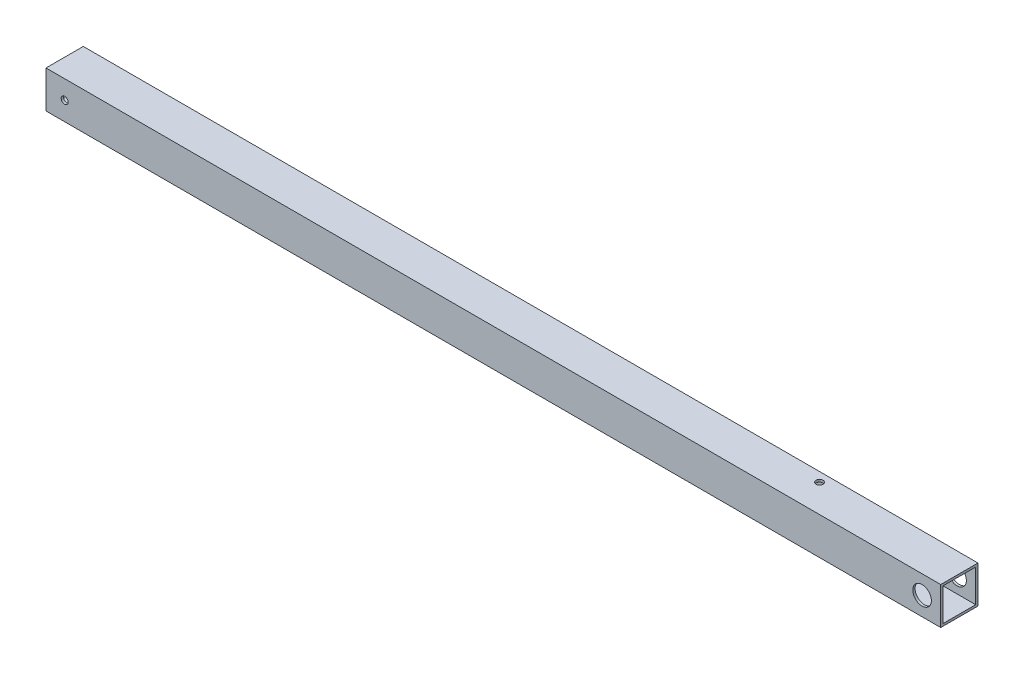
SolidWorks part; units mm, degrees
material "1060 Alloy"
ref_plane "Front Plane" through (0, 0, 0) normal (0, 0, 1) x (1, 0, 0)
ref_plane "Top Plane" through (0, 0, 0) normal (0, 1, 0) x (1, 0, 0)
ref_plane "Right Plane" through (0, 0, 0) normal (1, 0, 0) x (0, 0, -1)
sketch "Sketch1" plane through (0, 0, 0) normal (0, 0, 1) x (1, 0, 0)
  line L0 (0, -25.4) -> (609.6, -25.4)
  line L1 (609.6, -25.4) -> (609.6, 0)
  line L2 (609.6, 0) -> (0, 0)
  line L3 (0, 0) -> (0, -25.4)
extrude "Boss-Extrude1" add sketch "Sketch1" against normal blind 25.4
sketch "Sketch2" plane through (0, 0, 0) normal (-1, 0, 0) x (0, 0, 1)
  line L0 (-1.5875, -1.5875) -> (-23.8125, -1.5875)
  line L1 (-23.8125, -1.5875) -> (-23.8125, -23.8125)
  line L2 (-23.8125, -23.8125) -> (-1.5875, -23.8125)
  line L3 (-1.5875, -23.8125) -> (-1.5875, -1.5875)
extrude "Cut-Extrude1" cut sketch "Sketch2" against normal through all
hole_wizard "Hole1" positions "Sketch4" profile "Sketch3" legacy
sketch "Sketch4" plane through (0, -23.8125, 0) normal (0, 1, 0) x (1, 0, 0)
  point P0 (508, 19.05)
sketch "Sketch3" plane through (508, -23.8125, -19.05) normal (1, 0, 0) x (0, 0, 1)
  line L0 (0, 0) -> (0, 1.5875)
  line L1 (0, 1.5875) -> (2.4003, 1.5875)
  line L2 (2.4003, 1.5875) -> (2.4003, 0)
  line L3 (2.4003, 0) -> (0, 0)
  line L4 (0, 110) -> (0, -10) construction
  dimension "Diameter" = 4.8006
  dimension "Depth" = 1.5875
hole_wizard "M4 Clearance Hole1" positions "Sketch6" profile "Sketch5" hole size "M4" standard "ANSI Metric"
sketch "Sketch6" plane through (0, 0, -23.8125) normal (0, 0, 1) x (1, 0, 0)
  point P0 (12.7, -12.7)
sketch "Sketch5" plane through (12.7, -12.7, -23.8125) normal (1, 0, 0) x (0, -1, 0)
  line L0 (0, 0) -> (0, 1.5875)
  line L1 (0, 1.5875) -> (2.3812, 1.5875)
  line L2 (2.3812, 1.5875) -> (2.3812, 0)
  line L5 (2.3812, 0) -> (0, 0)
  line L11 (0, -6.35) -> (0, 107.95) construction
  dimension "Thru Hole Dia." = 4.7625
  dimension "Thru Hole Depth" = 1.5875
hole_wizard "Hole2" positions "Sketch8" profile "Sketch7" legacy
sketch "Sketch8" plane through (0, 0, -23.8125) normal (0, 0, 1) x (1, 0, 0)
  point P0 (596.9, -12.7)
sketch "Sketch7" plane through (596.9, -12.7, -23.8125) normal (1, 0, 0) x (0, -1, 0)
  line L0 (0, 0) -> (0, 1.5875)
  line L1 (0, 1.5875) -> (6.35, 1.5875)
  line L2 (6.35, 1.5875) -> (6.35, 0)
  line L3 (6.35, 0) -> (0, 0)
  line L4 (0, 110) -> (0, -10) construction
  dimension "Diameter" = 12.7
  dimension "Depth" = 1.5875
hole_wizard "M4 Clearance Hole2" positions "Sketch10" profile "Sketch9" hole size "M4" standard "ANSI Metric"
sketch "Sketch10" plane through (0, 0, 0) normal (0, 0, 1) x (1, 0, 0)
  point P0 (12.7, -12.7)
sketch "Sketch9" plane through (12.7, -12.7, 0) normal (1, 0, 0) x (0, -1, 0)
  line L0 (0, 0) -> (0, 25.4)
  line L1 (0, 25.4) -> (2.3812, 25.4)
  line L2 (2.3812, 25.4) -> (2.3812, 0)
  line L5 (2.3812, 0) -> (0, 0)
  line L11 (0, -6.35) -> (0, 107.95) construction
  dimension "Thru Hole Dia." = 4.7625
  dimension "Thru Hole Depth" = 25.4
hole_wizard "Hole3" positions "Sketch12" profile "Sketch11" legacy
sketch "Sketch12" plane through (0, 0, 0) normal (0, 0, 1) x (1, 0, 0)
  point P0 (596.9, -12.7)
sketch "Sketch11" plane through (596.9, -12.7, 0) normal (1, 0, 0) x (0, -1, 0)
  line L0 (0, 0) -> (0, 25.4)
  line L1 (0, 25.4) -> (6.35, 25.4)
  line L2 (6.35, 25.4) -> (6.35, 0)
  line L3 (6.35, 0) -> (0, 0)
  line L4 (0, 110) -> (0, -10) construction
  dimension "Diameter" = 12.7
  dimension "Depth" = 25.4
hole_wizard "Hole4" positions "Sketch14" profile "Sketch13" legacy
sketch "Sketch14" plane through (0, 0, 0) normal (0, 1, 0) x (1, 0, 0)
  point P0 (508, 19.05)
sketch "Sketch13" plane through (508, 0, -19.05) normal (1, 0, 0) x (0, 0, 1)
  line L0 (0, 0) -> (0, 25.4)
  line L1 (0, 25.4) -> (2.4003, 25.4)
  line L2 (2.4003, 25.4) -> (2.4003, 0)
  line L3 (2.4003, 0) -> (0, 0)
  line L4 (0, 110) -> (0, -10) construction
  dimension "Diameter" = 4.8006
  dimension "Depth" = 25.4
